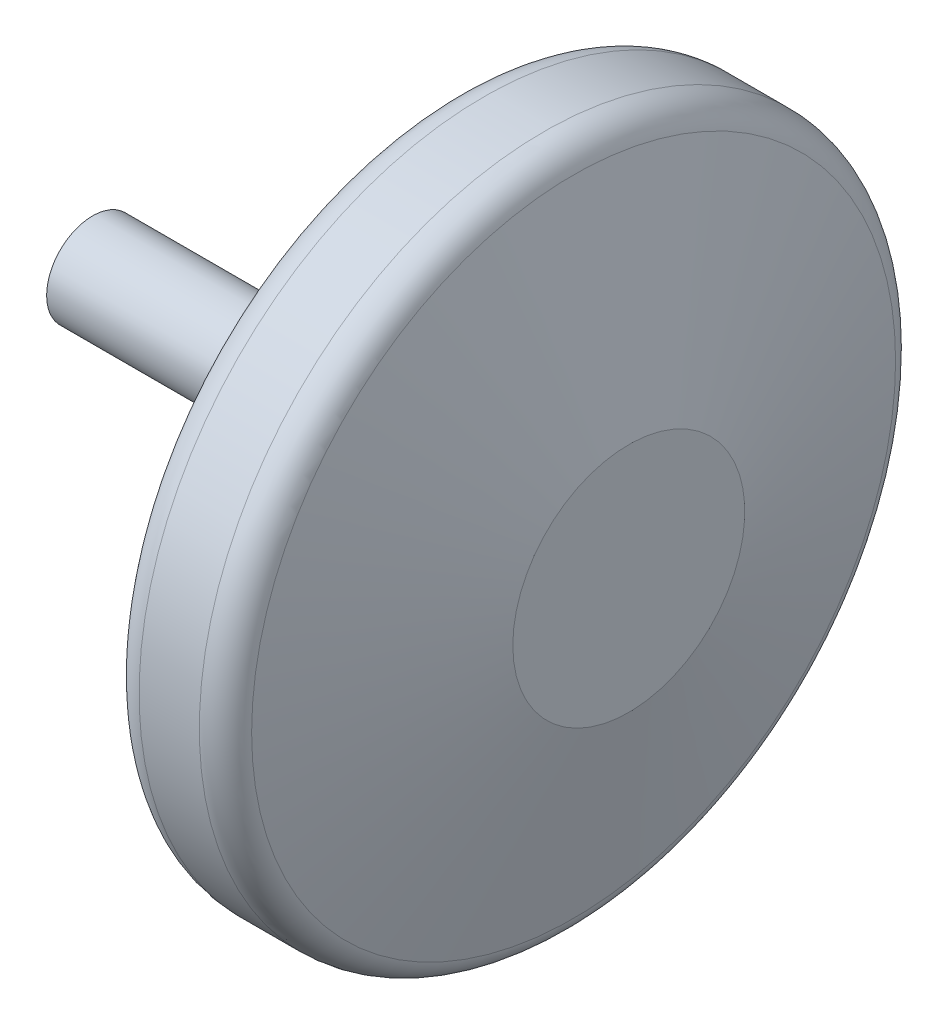
SolidWorks part; units mm, degrees
material "Полиамид ПА-6Б ТУ 6-05-988-87"
ref_plane "Plane1" through (0, 0, 0) normal (0, 0, 1) x (1, 0, 0)
ref_plane "Plane2" through (0, 0, 0) normal (0, 1, 0) x (1, 0, 0)
ref_plane "Plane3" through (0, 0, 0) normal (1, 0, 0) x (0, 0, -1)
sketch "Эскиз1" plane through (0, 0, 0) normal (0, 0, 1) x (1, 0, 0)
  line L0 (0, 0) -> (39.5937, 0) construction
  line L1 (0, 0) -> (0, 3)
  line L2 (0, 3) -> (20, 3)
  line L3 (20, 3) -> (20, 7.5718)
  line L5 (20, 7.5718) -> (24, 22.5)
  line L6 (24, 22.5) -> (31, 22.5)
  line L7 (31, 22.5) -> (31, 14) construction
  line L8 (31, 14) -> (26, 9) construction
  line L9 (26, 9) -> (26, 0) construction
  line L10 (0, 0) -> (26, 0)
  line L11 (31, 22.5) -> (35, 7.5718)
  line L12 (35, 7.5718) -> (35, 0)
  line L13 (35, 0) -> (26, 0)
  line L14 (20, 7.5718) -> (35, 7.5718) construction
  line L15 (27.5, 7.5718) -> (27.5, 32.6044) construction
  point P6 (30, 16.0371)
  point P17 (22.5, 32.6044)
  dimension "D3" = 20
  dimension "D4" = 15
  dimension "D2" = 6
  dimension "D5" = 15
  dimension "D6" = 45
  dimension "D7" = 7
  dimension "D8" = 5
  dimension "D9" = 28
  dimension "D10" = 18
  dimension "D11" = 35
revolve "Повернуть1" add sketch "Эскиз1" angle 360 about L0
fillet "Скругление1" radius 2 2 edges at (24, 0, 22.5) (31, 0, 22.5)
